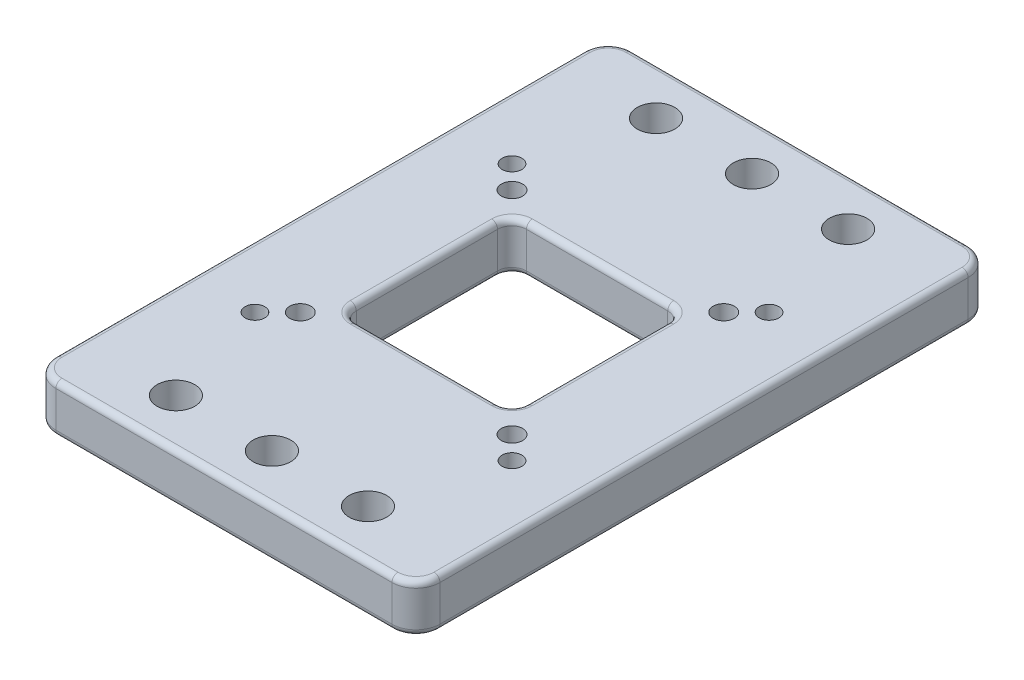
SolidWorks part; units mm, degrees
ref_plane "Front Plane" through (0, 0, 0) normal (0, 0, 1) x (1, 0, 0)
ref_plane "Top Plane" through (0, 0, 0) normal (0, 1, 0) x (1, 0, 0)
ref_plane "Right Plane" through (0, 0, 0) normal (1, 0, 0) x (0, 0, -1)
sketch "Sketch1" plane through (0, 0, 0) normal (0, 1, 0) x (1, 0, 0)
  line L0 (0, 0) -> (-9.2818, 0) construction
  line L1 (-17, 17) -> (17, 17) construction
  line L2 (-17, 17) -> (-17, -17) construction
  line L3 (-17, -17) -> (17, -17) construction
  line L4 (17, 17) -> (17, -17) construction
  line L5 (-17, 17) -> (17, -17) construction
  line L6 (-17, -17) -> (17, 17) construction
  line L7 (-14, 14) -> (14, 14) construction
  line L8 (-14, 14) -> (-14, -14) construction
  line L9 (-14, -14) -> (14, -14) construction
  line L10 (14, 14) -> (14, -14) construction
  line L11 (-14, 14) -> (14, -14) construction
  line L12 (-14, -14) -> (14, 14) construction
  line L17 (-11.25, 11.25) -> (11.25, 11.25)
  line L18 (-11.25, 11.25) -> (-11.25, -11.25)
  line L19 (-25.4, 38.1) -> (25.4, 38.1)
  line L20 (-25.4, 38.1) -> (-25.4, -38.1)
  line L21 (-25.4, -38.1) -> (25.4, -38.1)
  line L22 (25.4, 38.1) -> (25.4, -38.1)
  line L23 (-25.4, 38.1) -> (25.4, -38.1) construction
  line L24 (-25.4, -38.1) -> (25.4, 38.1) construction
  line L25 (-11.25, -11.25) -> (11.25, -11.25)
  line L26 (11.25, 11.25) -> (11.25, -11.25)
  line L27 (-11.25, 11.25) -> (11.25, -11.25) construction
  line L28 (-11.25, -11.25) -> (11.25, 11.25) construction
  line L29 (-12.7, 31.75) -> (0, 31.75) construction
  circle A0 centre (-17, 17) radius 1.3
  circle A1 centre (-17, -17) radius 1.3
  circle A2 centre (17, -17) radius 1.3
  circle A3 centre (17, 17) radius 1.3
  circle A4 centre (-14, 14) radius 1.4
  circle A5 centre (14, 14) radius 1.4
  circle A6 centre (14, -14) radius 1.4
  circle A7 centre (-14, -14) radius 1.4
  circle A8 centre (-12.7, 31.75) radius 2.4892
  circle A9 centre (0, 31.75) radius 2.4892
  circle A10 centre (12.7, 31.75) radius 2.4892
  circle A11 centre (12.7, -31.75) radius 2.4892
  circle A12 centre (0, -31.75) radius 2.4892
  circle A13 centre (-12.7, -31.75) radius 2.4892
  point P0 (0, 0)
  point P10 (0, 0)
  point P19 (0, 0)
  point P25 (0, 0)
  dimension "D3" = 2.6
  dimension "D6" = 2.8
  dimension "D11" = 4.9784
  dimension "D12" = 6.35
  dimension "D13" = 12.7
  dimension "D1" = 34
  dimension "D2" = 34
  dimension "D4" = 28
  dimension "D5" = 28
  dimension "D7" = 50.8
  dimension "D8" = 76.2
  dimension "D9" = 22.5
  dimension "D10" = 22.5
  dimension "D15" = 12.7
  dimension "D14" = 3
extrude "Boss-Extrude1" add sketch "Sketch1" along normal blind 6.35
fillet "Fillet1" radius 3.175 4 edges at (25.4, 3.175, 38.1) (-25.4, 3.175, 38.1) (25.4, 3.175, -38.1) (-25.4, 3.175, -38.1)
fillet "Fillet2" radius 1.905 4 edges at (-11.25, 3.175, -11.25) (-11.25, 3.175, 11.25) (11.25, 3.175, -11.25) (11.25, 3.175, 11.25)
fillet "Fillet3" radius 0.7937 32 edges at (-24.4701, 0, -37.1701) (0, 0, -38.1) (24.4701, 0, -37.1701) (25.4, 0, 0) (24.4701, 0, 37.1701) (0, 0, 38.1) (-24.4701, 0, 37.1701) (-24.4701, 6.35, -37.1701) (0, 6.35, -38.1) (24.4701, 6.35, -37.1701) (25.4, 6.35, 0) (24.4701, 6.35, 37.1701) (0, 6.35, 38.1) (-24.4701, 6.35, 37.1701) (-25.4, 0, 0) (-25.4, 6.35, 0) (-10.692, 6.35, -10.692) (-11.25, 6.35, 0) (-10.692, 6.35, 10.692) (0, 6.35, 11.25) (10.692, 6.35, 10.692) (11.25, 6.35, 0) (10.692, 6.35, -10.692) (-10.692, 0, -10.692) (-11.25, 0, 0) (-10.692, 0, 10.692) (0, 0, 11.25) (10.692, 0, 10.692) (11.25, 0, 0) (10.692, 0, -10.692) (0, 6.35, -11.25) (0, 0, -11.25)
